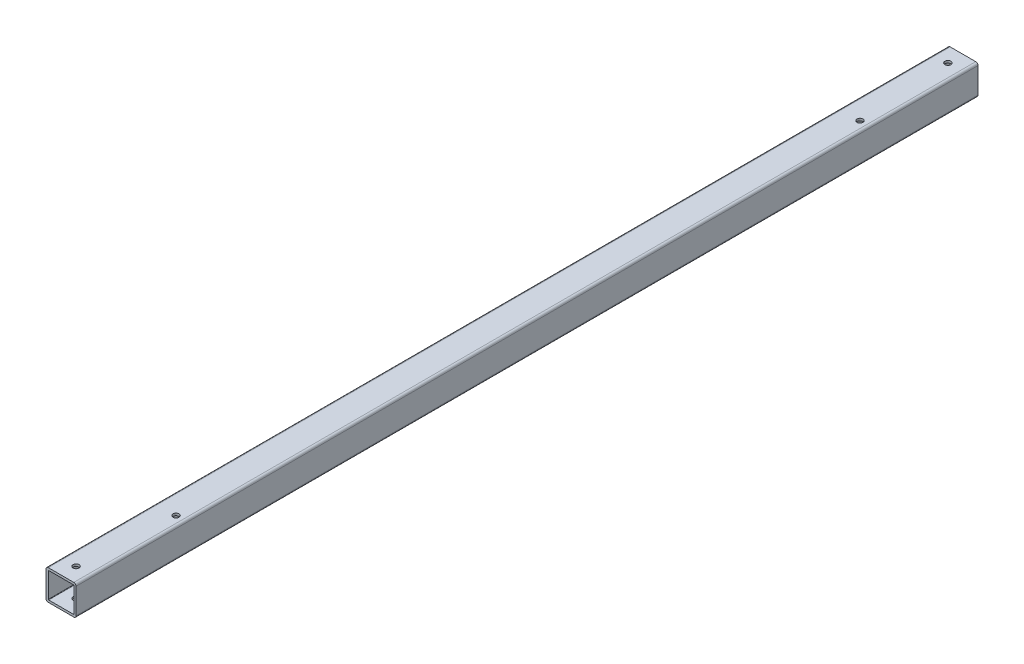
SolidWorks part; units mm, degrees
ref_plane "Front Plane" through (0, 0, 0) normal (0, 0, 1) x (1, 0, 0)
ref_plane "Top Plane" through (0, 0, 0) normal (0, 1, 0) x (1, 0, 0)
ref_plane "Right Plane" through (0, 0, 0) normal (1, 0, 0) x (0, 0, -1)
sketch "Sketch1" plane through (0, 0, 0) normal (0, 0, 1) x (1, 0, 0)
  line L1 (-20, 20) -> (20, 20)
  line L2 (-20, 20) -> (-20, -20)
  line L3 (-20, -20) -> (20, -20)
  line L4 (20, 20) -> (20, -20)
  line L5 (-20, 20) -> (20, -20) construction
  line L6 (-20, -20) -> (20, 20) construction
  point P0 (0, 0)
  dimension "D1" = 40
  dimension "D2" = 40
extrude "Extrude-Thin1" add sketch "Sketch1" along normal blind 1200 thin
fillet "Fillet1" radius 0.5 4 edges at (-17, -17, 600) (-17, 17, 600) (17, 17, 600) (17, -17, 600)
fillet "Fillet2" radius 3 4 edges at (20, -20, 600) (-20, -20, 600) (20, 20, 600) (-20, 20, 600)
hole_wizard "Ø8.0 (8) Diameter Hole1" positions "Sketch4" profile "Sketch3" hole size "Ø8.0" standard "ANSI Metric" end condition through all
sketch "Sketch4" plane through (0, 20, 0) normal (0, 1, 0) x (1, 0, 0)
  line L2 (0, 0) -> (0, -1200) construction
  line L3 (17, -1200) -> (-17, -1200) construction
  line L5 (17, 0) -> (-17, 0) construction
  point P0 (0, -20)
  point P2 (0, -1180)
  dimension "D1" = 20
  dimension "D2" = 20
sketch "Sketch3" plane through (0, 20, 20) normal (1, 0, 0) x (0, 0, 1)
  line L0 (0, 0) -> (0, 40)
  line L1 (0, 40) -> (4, 40)
  line L2 (4, 40) -> (4, 0)
  line L5 (4, 0) -> (0, 0)
  line L11 (0, -6.35) -> (0, 107.95) construction
  dimension "Thru Hole Dia." = 8
  dimension "Thru Hole Depth" = 40
hole_wizard "Ø8.0 (8) Diameter Hole2" positions "Sketch6" profile "Sketch5" hole size "Ø8.0" standard "ANSI Metric" end condition through all
sketch "Sketch6" plane through (0, 20, 0) normal (0, 1, 0) x (1, 0, 0)
  line L0 (20, 0) -> (20, -1200) construction
  circle A0 centre (0, -20) radius 4 construction
  circle A1 centre (0, -1180) radius 4 construction
  point P0 (8, -1055)
  point P2 (8, -145)
  dimension "D1" = 125
  dimension "D4" = 12
  dimension "D2" = 12
  dimension "D3" = 125
sketch "Sketch5" plane through (8, 20, 1055) normal (1, 0, 0) x (0, 0, 1)
  line L0 (0, 0) -> (0, 40)
  line L1 (0, 40) -> (4, 40)
  line L2 (4, 40) -> (4, 0)
  line L5 (4, 0) -> (0, 0)
  line L11 (0, -6.35) -> (0, 107.95) construction
  dimension "Thru Hole Dia." = 8
  dimension "Thru Hole Depth" = 40
equation "\"a\"= \"Beam Profile@Plasma Beta.Assembly\""
equation "\"b\"= 3"
equation "\"L\"= \"Width@Plasma Beta.Assembly\""
equation "\"D2@Sketch1\"=\"a\""
equation "\"D1@Sketch1\"=\"a\""
equation "\"D1@Extrude-Thin1\"=\"L\""
equation "\"D5@Extrude-Thin1\"=\"b\""
equation "\"D1@Fillet2\"=\"b\""
